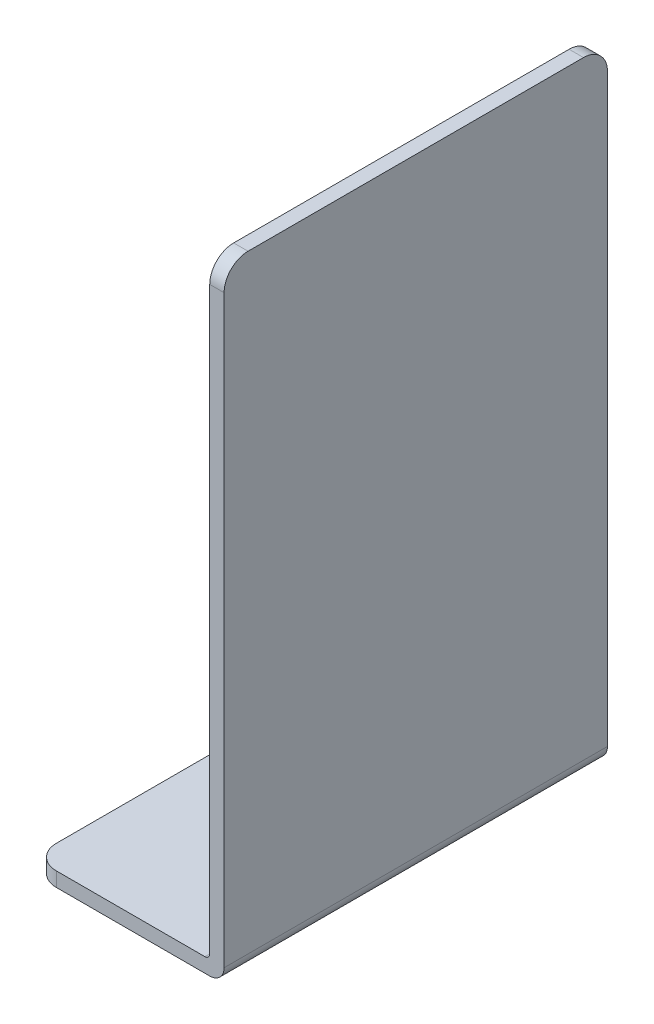
SolidWorks part; units mm, degrees
material "1.0037 (S235JR)"
ref_plane "Front Plane" through (0, 0, 0) normal (0, 0, 1) x (1, 0, 0)
ref_plane "Top Plane" through (0, 0, 0) normal (0, 1, 0) x (1, 0, 0)
ref_plane "Right Plane" through (0, 0, 0) normal (1, 0, 0) x (0, 0, -1)
sketch "Sketch1" plane through (0, 0, 0) normal (0, 0, 1) x (1, 0, 0)
  line L0 (0, 0) -> (0, -254)
  line L1 (-6, -260) -> (-80, -260)
  line L2 (-80, -260) -> (-80, -254)
  line L3 (-80, -254) -> (-8, -254)
  line L4 (-6, -252) -> (-6, 0)
  line L5 (-6, 0) -> (0, 0)
  arc A0 (0, -254) -> (-6, -260) centre (-6, -254) cw
  arc A1 (-8, -254) -> (-6, -252) centre (-8, -252) ccw
  point P10 (-9.5573, -250.4427)
  dimension "D4" = 2
  dimension "D1" = 6
  dimension "D2" = 80
  dimension "D3" = 254
extrude "Boss-Extrude1" add sketch "Sketch1" along normal blind 160
fillet "Fillet1" radius 10 4 edges at (-80, -257, 160) (-80, -257, 0) (-3, 0, 0) (-3, 0, 160)
